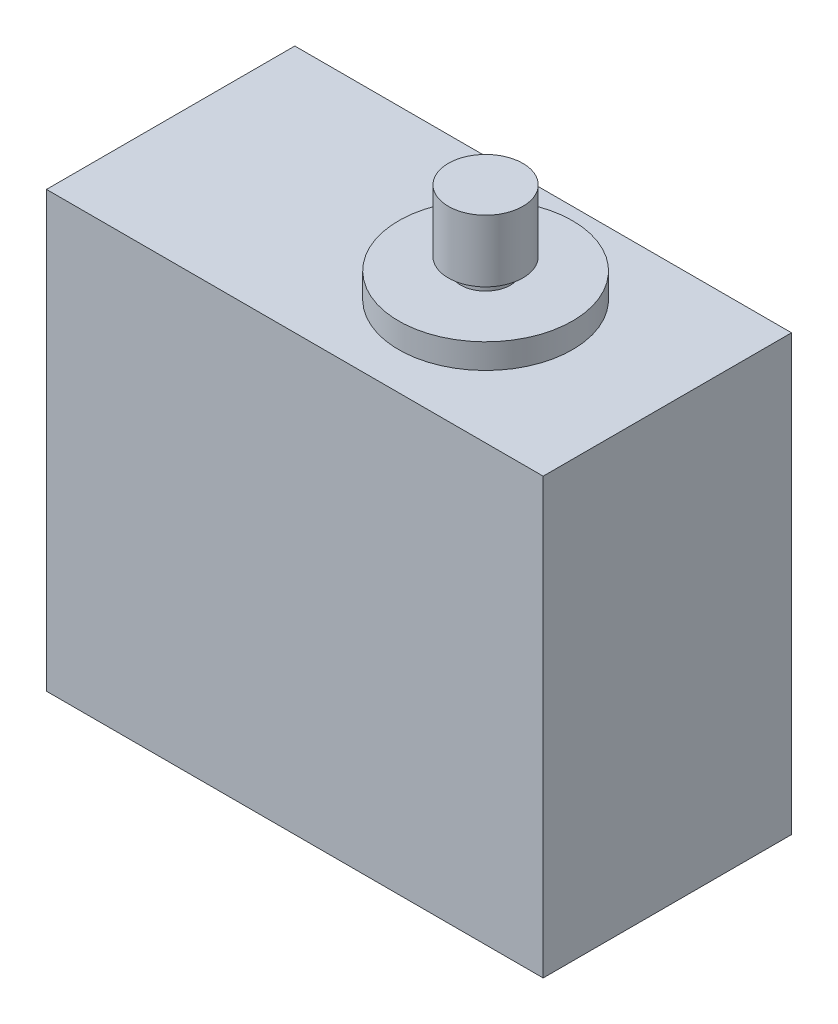
SolidWorks part; units mm, degrees
ref_plane "正面" through (0, 0, 0) normal (0, 0, 1) x (1, 0, 0)
ref_plane "平面" through (0, 0, 0) normal (0, 1, 0) x (1, 0, 0)
ref_plane "右側面" through (0, 0, 0) normal (1, 0, 0) x (0, 0, -1)
sketch "ｽｹｯﾁ1" plane through (0, 0, 0) normal (0, 0, 1) x (1, 0, 0)
  line L1 (0, 0) -> (40, 0)
  line L2 (0, 0) -> (0, 35)
  line L3 (0, 35) -> (40, 35)
  line L4 (40, 0) -> (40, 35)
  dimension "D1" = 40
  dimension "D2" = 35
extrude "ﾎﾞｽ - 押し出し1" add sketch "ｽｹｯﾁ1" along normal mid plane 20
sketch "ｽｹｯﾁ2" plane through (0, 0, 0) normal (0, 0, 1) x (1, 0, 0)
  line L0 (25.3642, 35) -> (25.3642, 43)
  line L1 (40, 35) -> (0, 35) construction
  line L2 (25.3642, 43) -> (22.3642, 43)
  line L3 (22.3642, 43) -> (22.3642, 38)
  line L4 (22.3642, 38) -> (23.3642, 38)
  line L5 (23.3642, 38) -> (23.3642, 37)
  line L6 (23.3642, 37) -> (18.3642, 37)
  line L7 (18.3642, 37) -> (18.3642, 35)
  line L8 (18.3642, 35) -> (25.3642, 35)
  point P10 (29.456, 35)
  point P11 (25.3642, 43)
  point P12 (0, 0)
  dimension "D1" = 5
  dimension "D2" = 3
  dimension "D3" = 1
  dimension "D4" = 1
  dimension "D5" = 2
  dimension "D6" = 7
revolve "回転1" add sketch "ｽｹｯﾁ2" angle 360 about L0
